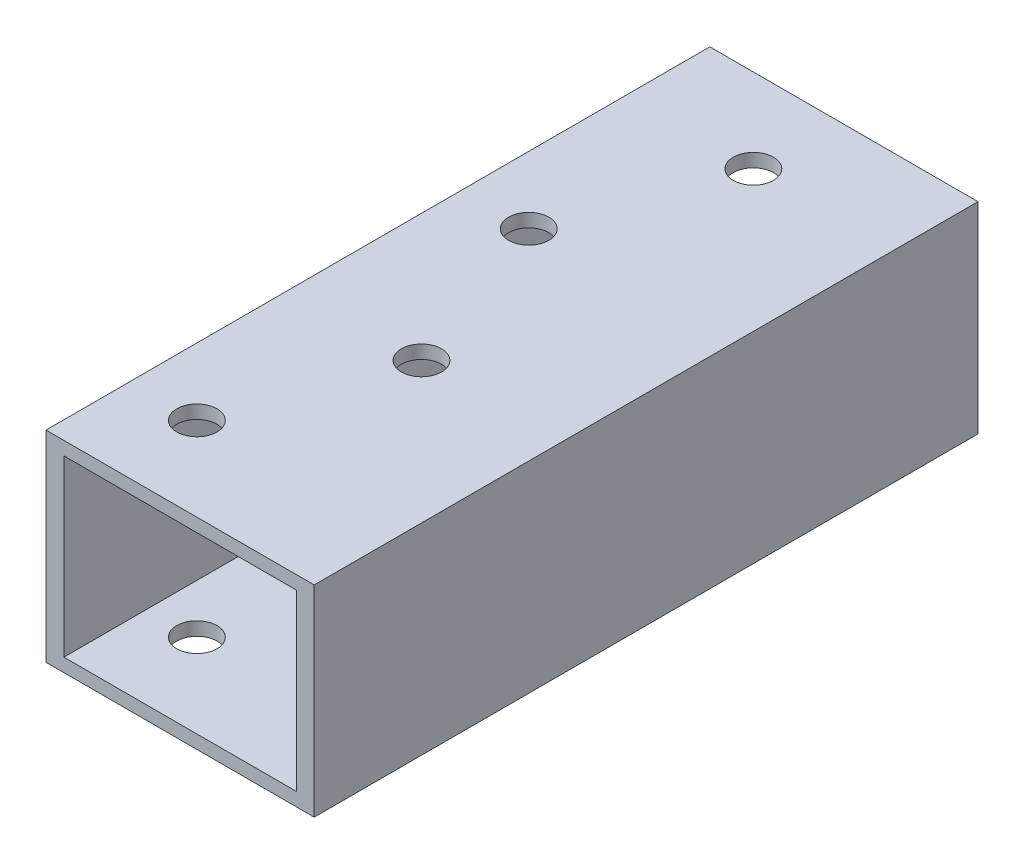
SolidWorks part; units mm, degrees
ref_plane "前视基准面" through (0, 0, 0) normal (0, 0, 1) x (1, 0, 0)
ref_plane "上视基准面" through (0, 0, 0) normal (0, 1, 0) x (1, 0, 0)
ref_plane "右视基准面" through (0, 0, 0) normal (1, 0, 0) x (0, 0, -1)
sketch "草图1" plane through (0, 0, 0) normal (0, 0, 1) x (1, 0, 0)
  line L1 (20, -15) -> (-20, -15)
  line L2 (20, -15) -> (20, 15)
  line L3 (20, 15) -> (-20, 15)
  line L4 (-20, -15) -> (-20, 15)
  line L5 (20, -15) -> (-20, 15) construction
  line L6 (20, 15) -> (-20, -15) construction
  line L7 (17.3333, -13) -> (-17.3333, -13)
  line L8 (17.3333, -13) -> (17.3333, 13)
  line L9 (17.3333, 13) -> (-17.3333, 13)
  line L10 (-17.3333, -13) -> (-17.3333, 13)
  line L11 (17.3333, -13) -> (-17.3333, 13) construction
  line L12 (17.3333, 13) -> (-17.3333, -13) construction
  point P0 (0, 0)
  point P6 (0, 0)
  dimension "D1" = 30
  dimension "D2" = 40
  dimension "D3" = 26
extrude "凸台-拉伸1" add sketch "草图1" along normal blind 99
sketch "草图3" plane through (0, 15, 0) normal (0, 1, 0) x (1, 0, 0)
  line L0 (20, -99) -> (-20, -99) construction
  line L1 (-20, -99) -> (-20, 0) construction
  circle A0 centre (-10, -86.5) radius 3
  circle A1 centre (-1, -62) radius 3
  circle A2 centre (-10, -37) radius 3
  circle A3 centre (-1, -12.5) radius 3
  dimension "D1" = 24.5
  dimension "D2" = 24.5
  dimension "D3" = 25
  dimension "D4" = 12.5
  dimension "D5" = 10
  dimension "D6" = 10
  dimension "D7" = 9
  dimension "D8" = 9
  dimension "D9" = 6
  dimension "D10" = 6
  dimension "D11" = 6
  dimension "D12" = 6
extrude "切除-拉伸1" cut sketch "草图3" against normal through all
